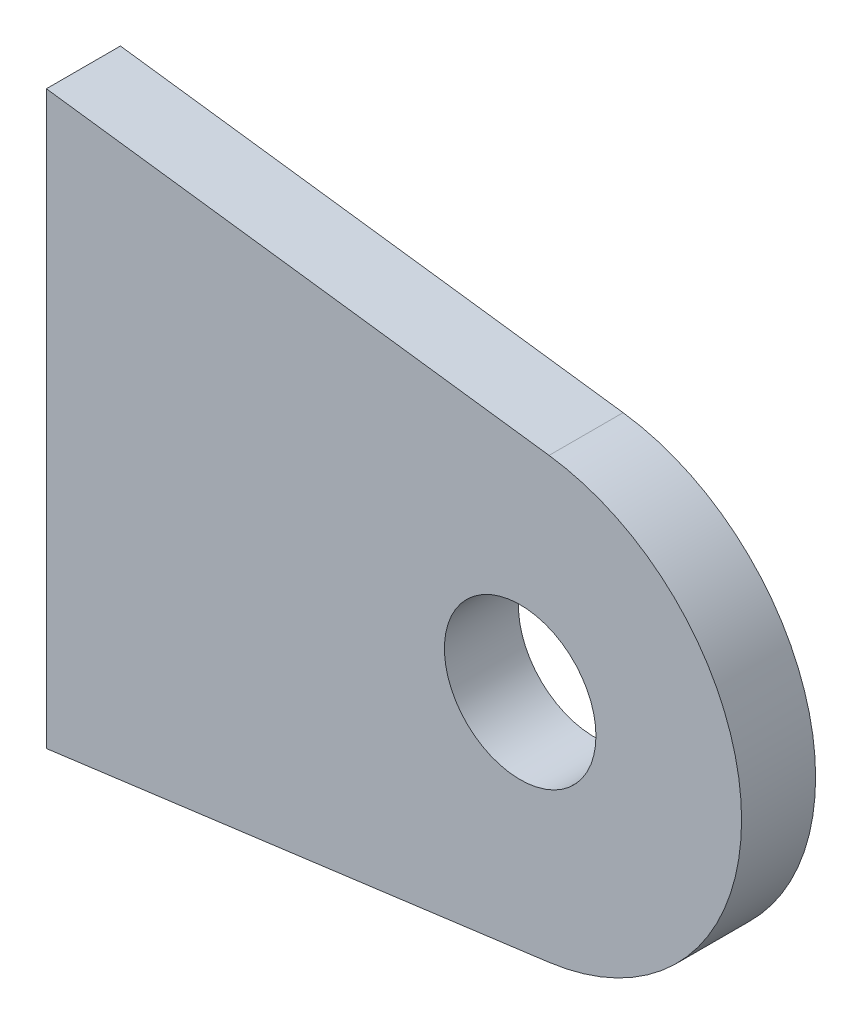
SolidWorks part; units mm, degrees
material "AISI 4130 Steel, annealed at 865C"
ref_plane "X-Y Datum" through (0, 0, 0) normal (0, 0, 1) x (1, 0, 0)
ref_plane "X-Z Datum" through (0, 0, 0) normal (0, 1, 0) x (1, 0, 0)
ref_plane "Y-Z Datum" through (0, 0, 0) normal (1, 0, 0) x (0, 0, -1)
sketch "Sketch1" plane through (-1053.7408, 0, 0) normal (0, 0, 1) x (1, 0, 0)
  line L0 (1054.9803, -9.4147) -> (1033.4208, -12.2531)
  line L1 (1054.9803, 9.4147) -> (1033.4208, 12.2531)
  line L2 (1033.4208, -12.2531) -> (1033.4208, 12.2531)
  circle A0 centre (1053.7408, 0) radius 3.25
  circle A1 centre (1053.7408, 0) radius 9.4959
  circle A4 centre (1053.7408, 0) radius 11.43 construction
  dimension "D3" = 18.9919
  dimension "D4" = 6.5
  dimension "D5" = 22.86
  dimension "D1" = 15
  dimension "D2" = 20.32
extrude "Boss-Extrude1" add sketch "Sketch1" along normal blind 3.175
